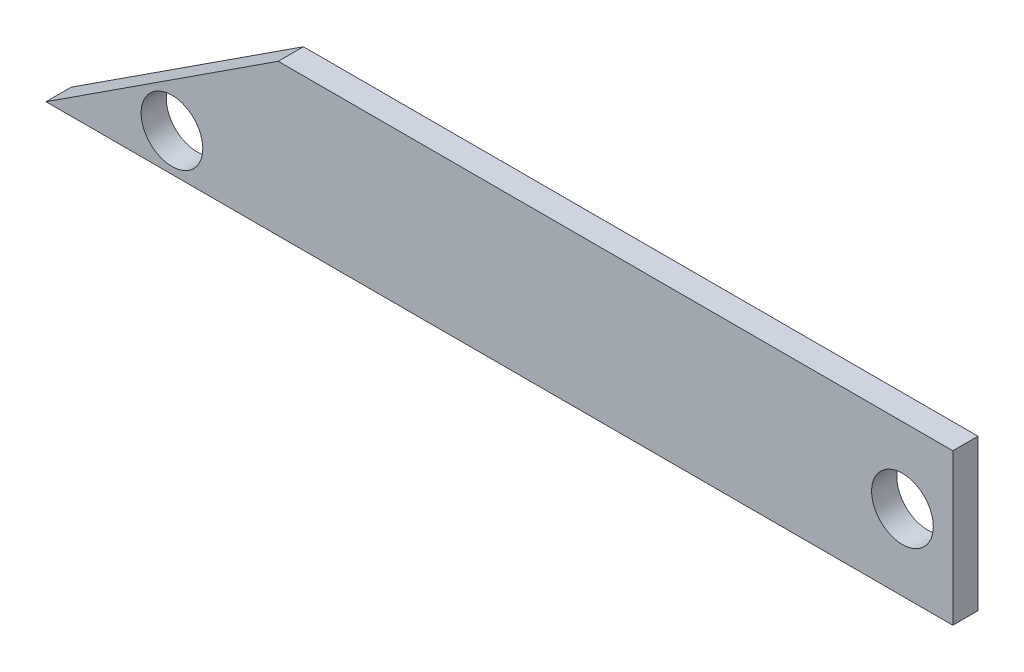
SolidWorks part; units mm, degrees
material "Beech"
ref_plane "Front Plane" through (0, 0, 0) normal (0, 0, 1) x (1, 0, 0)
ref_plane "Top Plane" through (0, 0, 0) normal (0, 1, 0) x (1, 0, 0)
ref_plane "Right Plane" through (0, 0, 0) normal (1, 0, 0) x (0, 0, -1)
sketch "Sketch1" plane through (0, 0, 0) normal (0, 0, 1) x (1, 0, 0)
  line L1 (0, 0) -> (457.2, 0)
  line L2 (0, 0) -> (0, 76.2)
  line L3 (0, 76.2) -> (457.2, 76.2)
  line L4 (457.2, 0) -> (457.2, 76.2)
  dimension "D1" = 76.2
  dimension "D2" = 457.2
extrude "Boss-Extrude1" add sketch "Sketch1" along normal blind 12.7
sketch "Sketch2" plane through (0, 0, 12.7) normal (0, 0, 1) x (1, 0, 0)
  line L0 (0, 0) -> (117.0882, 76.2)
  line L1 (457.2, 76.2) -> (0, 76.2) construction
  line L2 (117.0882, 76.2) -> (0, 76.2)
  line L3 (0, 76.2) -> (0, 0)
  dimension "D1" = 139.7
extrude "Cut-Extrude1" cut sketch "Sketch2" against normal blind 12.7
sketch "Sketch3" plane through (0, 0, 12.7) normal (0, 0, 1) x (1, 0, 0)
  line L0 (0, 0) -> (457.2, 0) construction
  line L1 (457.2, 0) -> (457.2, 76.2) construction
  circle A0 centre (63.5, 19.05) radius 15.5575
  circle A1 centre (431.8, 38.1) radius 15.5575
  dimension "D1" = 31.115
  dimension "D4" = 31.115
  dimension "D5" = 25.4
  dimension "D2" = 19.05
  dimension "D3" = 63.5
  dimension "D6" = 38.1
extrude "Cut-Extrude2" cut sketch "Sketch3" against normal blind 12.7
